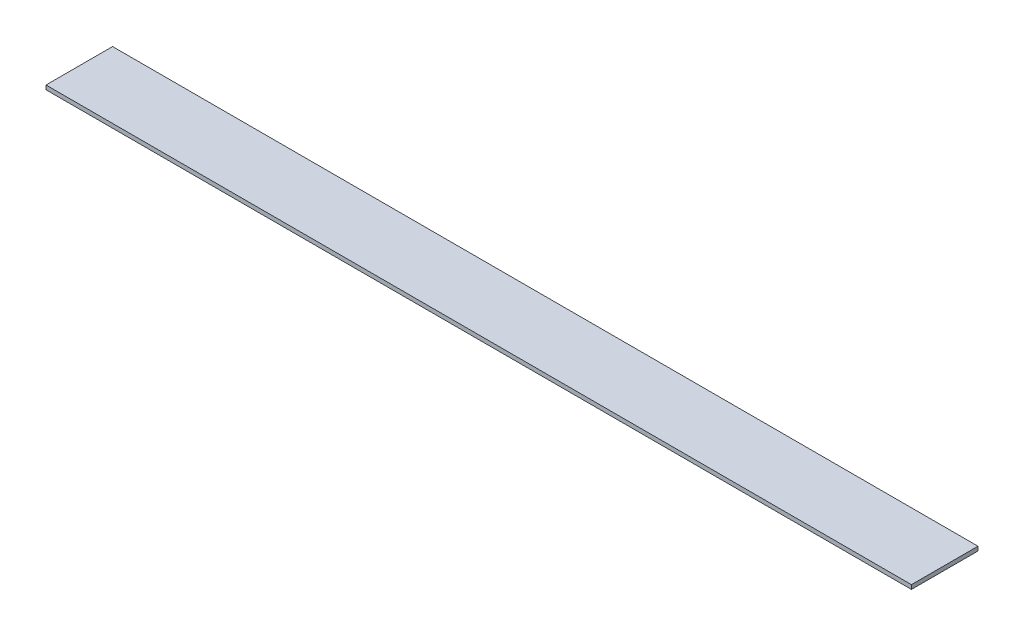
SolidWorks part; units mm, degrees
material "Nylon 101"
ref_plane "Front Plane" through (0, 0, 0) normal (0, 0, 1) x (1, 0, 0)
ref_plane "Top Plane" through (0, 0, 0) normal (0, 1, 0) x (1, 0, 0)
ref_plane "Right Plane" through (0, 0, 0) normal (1, 0, 0) x (0, 0, -1)
sketch "Sketch1" plane through (0, 0, 0) normal (0, 1, 0) x (1, 0, 0)
  line L1 (0, 0) -> (330.2, 0)
  line L2 (0, 0) -> (0, 25.4)
  line L3 (0, 25.4) -> (330.2, 25.4)
  line L4 (330.2, 0) -> (330.2, 25.4)
  dimension "D1" = 25.4
  dimension "D2" = 330.2
extrude "Boss-Extrude1" add sketch "Sketch1" along normal blind 1.5875
